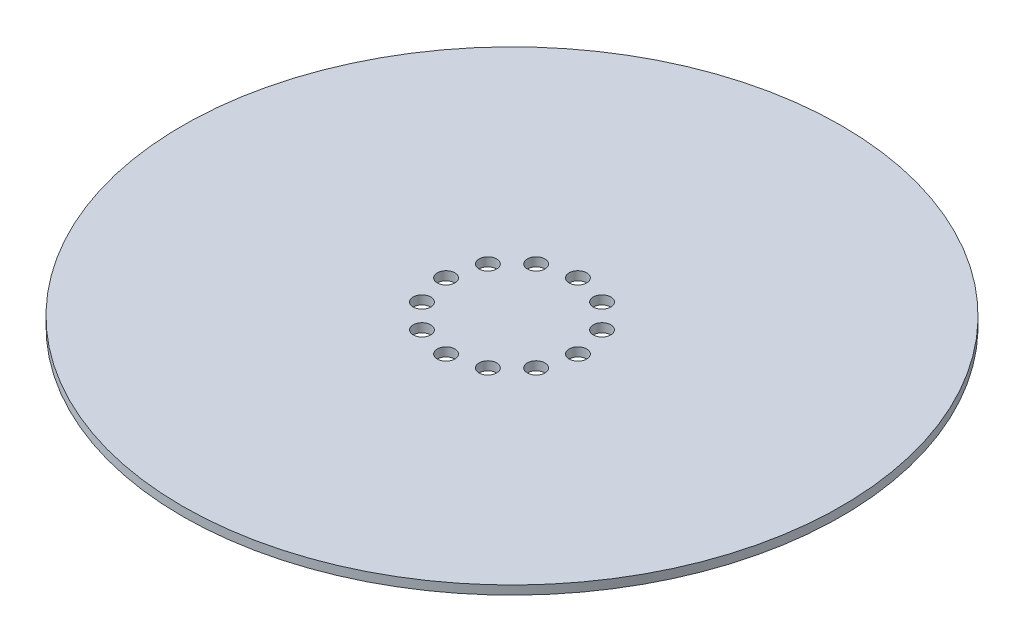
SolidWorks part; units mm, degrees
ref_plane "Front Plane" through (0, 0, 0) normal (0, 0, 1) x (1, 0, 0)
ref_plane "Top Plane" through (0, 0, 0) normal (0, 1, 0) x (1, 0, 0)
ref_plane "Right Plane" through (0, 0, 0) normal (1, 0, 0) x (0, 0, -1)
sketch "Sketch1" plane through (0, 0, 0) normal (0, 1, 0) x (1, 0, 0)
  circle A0 centre (0, 0) radius 300
  dimension "D1" = 600
extrude "Boss-Extrude1" add sketch "Sketch1" along normal blind 8
sketch "Sketch2" plane through (0, 0, 0) normal (0, -1, 0) x (1, 0, 0)
  circle A0 centre (0, 60) radius 8
  circle A8 centre (30, 51.9615) radius 8
  circle A9 centre (51.9615, 30) radius 8
  circle A10 centre (60, 0) radius 8
  circle A11 centre (51.9615, -30) radius 8
  circle A12 centre (30, -51.9615) radius 8
  circle A13 centre (0, -60) radius 8
  circle A14 centre (-30, -51.9615) radius 8
  circle A15 centre (-51.9615, -30) radius 8
  circle A16 centre (-60, 0) radius 8
  circle A17 centre (-51.9615, 30) radius 8
  circle A18 centre (-30, 51.9615) radius 8
  point P20 (0, 0)
  point P29 (0, 0)
  dimension "D1" = 16
  dimension "D2" = 60
  dimension "D3" = 12
extrude "Cut-Extrude1" cut sketch "Sketch2" against normal through all
